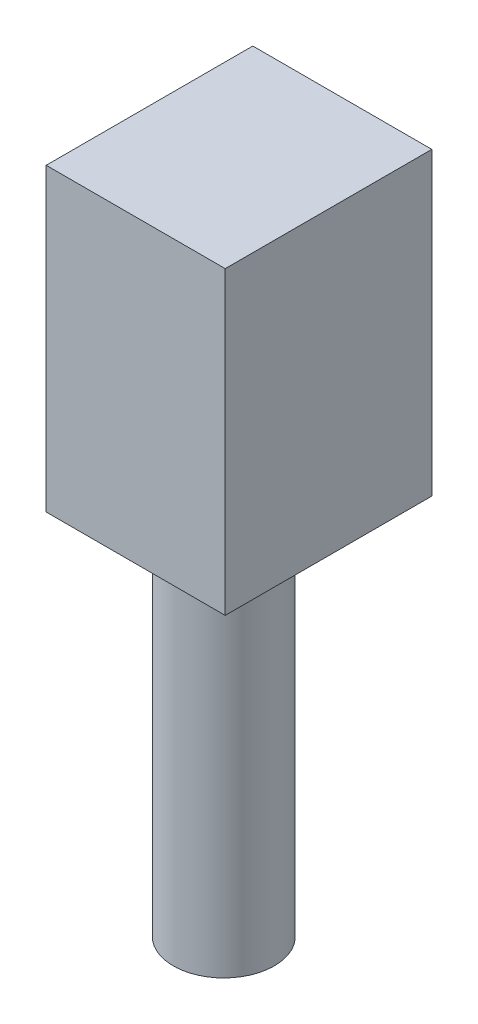
SolidWorks part; units mm, degrees
ref_plane "Front Plane" through (0, 0, 0) normal (0, 0, 1) x (1, 0, 0)
ref_plane "Top Plane" through (0, 0, 0) normal (0, 1, 0) x (1, 0, 0)
ref_plane "Right Plane" through (0, 0, 0) normal (1, 0, 0) x (0, 0, -1)
sketch "Sketch1" plane through (0, 0, 0) normal (0, 1, 0) x (1, 0, 0)
  line L1 (-51.3418, -47.7083) -> (72.3562, -47.7083)
  line L2 (-51.3418, -47.7083) -> (-51.3418, 95.0397)
  line L3 (-51.3418, 95.0397) -> (72.3562, 95.0397)
  line L4 (72.3562, -47.7083) -> (72.3562, 95.0397)
  dimension "D1" = 123.698
  dimension "D2" = 142.748
extrude "Extrude1" add sketch "Sketch1" along normal blind 207.518
sketch "Sketch2" plane through (0, 0, 0) normal (0, -1, 0) x (1, 0, 0)
  line L0 (-51.3418, -23.6657) -> (72.3562, -23.6657) construction
  line L1 (-51.3418, -95.0397) -> (-51.3418, 47.7083) construction
  line L2 (72.3562, 47.7083) -> (72.3562, -95.0397) construction
  circle A0 centre (0, -23.6657) radius 34.925
  dimension "D1" = 69.85
extrude "Extrude2" add sketch "Sketch2" along normal blind 264.16
